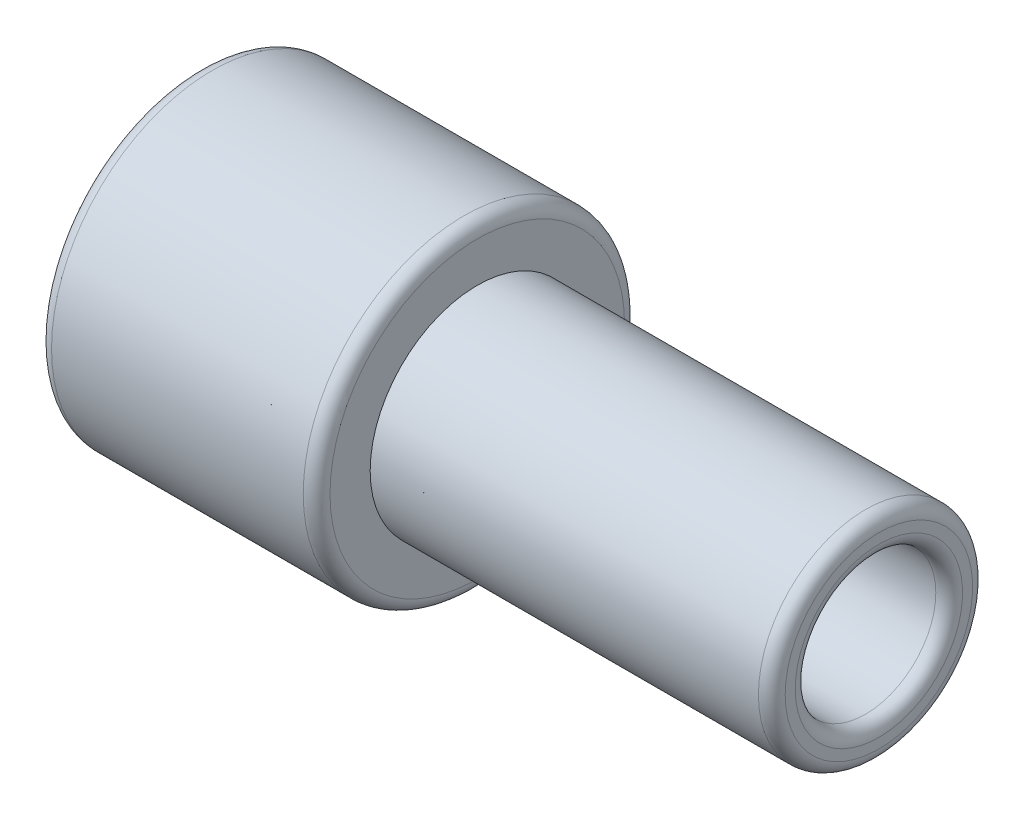
SolidWorks part; units mm, degrees
ref_plane "Front Plane" through (0, 0, 0) normal (0, 0, 1) x (1, 0, 0)
ref_plane "Top Plane" through (0, 0, 0) normal (0, 1, 0) x (1, 0, 0)
ref_plane "Right Plane" through (0, 0, 0) normal (1, 0, 0) x (0, 0, -1)
sketch "Sketch1" plane through (0, 0, 0) normal (0, 0, 1) x (1, 0, 0)
  line L0 (-1.1743, 0) -> (2.2457, 0) construction
  line L1 (11.4, 4) -> (-3.6, 4)
  line L2 (-3.6, 4) -> (-3.6, 6)
  line L3 (-3.6, 6) -> (-14, 6)
  line L4 (-14, 6) -> (-14, 0)
  line L5 (-14, 0) -> (11.4, 0)
  line L6 (11.4, 0) -> (11.4, 4)
  line L7 (3.6, 4.1) -> (3.6, 6)
  line L8 (3.6, 6) -> (14, 6)
  line L9 (14, 6) -> (14, 0)
  line L10 (14, 0) -> (11.5, 0)
  line L11 (11.5, 0) -> (11.5, 4.1)
  line L12 (11.5, 4.1) -> (3.6, 4.1)
  line L13 (-3.6, 6) -> (3.6, 6) construction
  line L14 (0, 0) -> (0, 6) construction
  dimension "D1" = 0.1
  dimension "D2" = 0.1
  dimension "D3" = 7.2
  dimension "D4" = 28
  dimension "D5" = 4
  dimension "D6" = 2
  dimension "D7" = 2.5
revolve "Revolve1" add sketch "Sketch1" angle 360 about L0
sketch "Sketch2" plane through (0, 0, 0) normal (1, 0, 0) x (0, 0, -1)
  circle A0 centre (0, 0) radius 2.625
  dimension "D1" = 5.25
extrude "Cut-Extrude1" cut sketch "Sketch2" against normal through all both and the other way through all
fillet "Fillet1" radius 0.5 5 edges at (11.4, 0, 4) (11.4, 0, -2.625) (-3.6, 0, 6) (-14, 0, -2.625) (-14, 0, 6)
